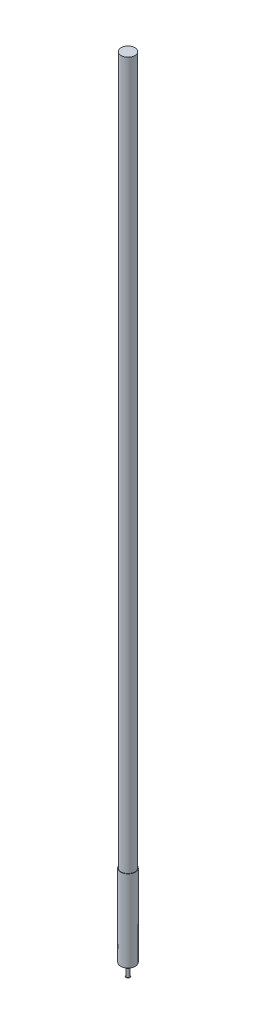
SolidWorks part; units mm, degrees
ref_plane "Front" through (0, 0, 0) normal (0, 0, 1) x (1, 0, 0)
ref_plane "Top" through (0, 0, 0) normal (0, 1, 0) x (1, 0, 0)
ref_plane "Right" through (0, 0, 0) normal (1, 0, 0) x (0, 0, -1)
ref_plane "Plane1" through (0, 0, 0) normal (0, -1, 0) x (1, 0, 0)
sketch "Sketch2" plane through (0, 0, 0) normal (1, 0, 0) x (0, 0, -1)
  line L0 (0, 105.4241) -> (0, 0) construction
  line L1 (0, 0) -> (16.6745, 0) construction
  line L2 (0.925, -4.4387) -> (0.925, 5.95)
  line L3 (0.925, 5.95) -> (0.875, 5.95)
  line L4 (0.875, 5.95) -> (0.875, 95.95)
  line L5 (0.875, 95.95) -> (0, 95.95)
  line L6 (0, 95.95) -> (0, -6.1)
  line L7 (0, -6.1) -> (-0.1524, -6.1) construction
  line L8 (0.25, -6) -> (0.2, -6)
  line L9 (0.2, -6) -> (0.2, -5)
  line L10 (0.2, -5) -> (0.925, -4.4387)
  arc A0 (0, -6.1) -> (0.25, -6) centre (0, -5.7375) ccw
  dimension "D7" = 90
  dimension "D1" = 1.85
  dimension "D2" = 6
  dimension "D3" = 0.4
  dimension "D4" = 52.253
  dimension "D5" = 0.5
  dimension "D6" = 0.1
  dimension "D8" = 5.95
  dimension "D9" = 1
  dimension "D10" = 1.75
revolve "Revolve1" add sketch "Sketch2" angle 360 about L0
